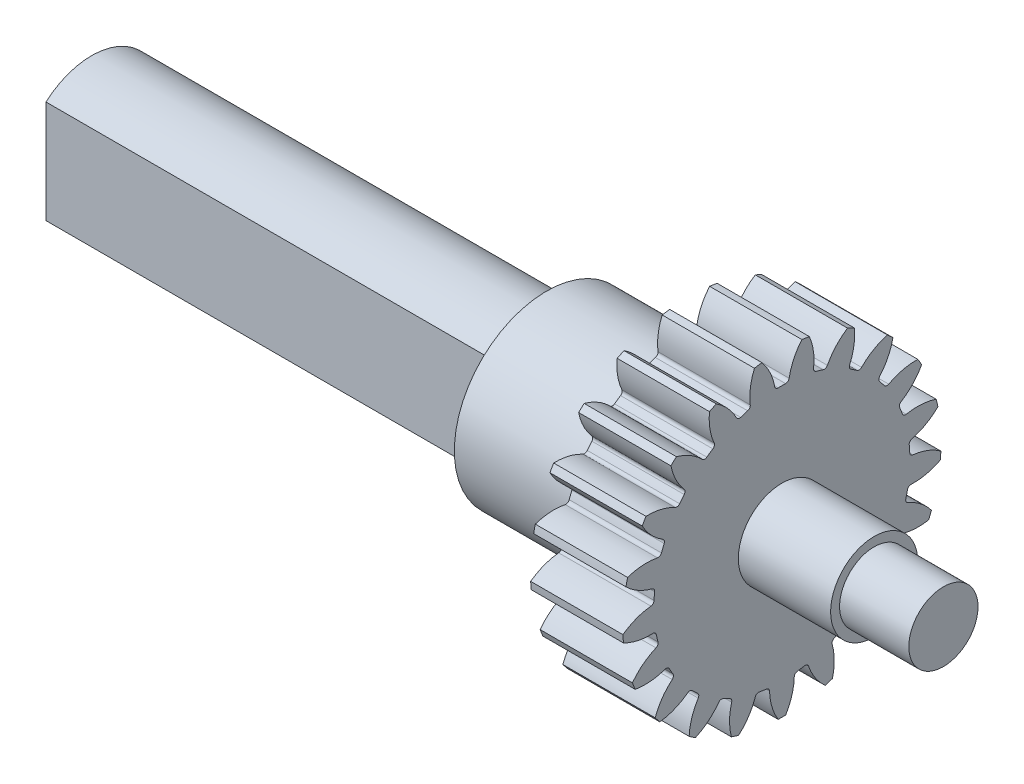
SolidWorks part; units mm, degrees
material "1.7003 (38Cr2)"
ref_plane "Plane1" through (0, 0, 0) normal (0, 0, 1) x (1, 0, 0)
ref_plane "Plane2" through (0, 0, 0) normal (0, 1, 0) x (1, 0, 0)
ref_plane "Plane3" through (0, 0, 0) normal (1, 0, 0) x (0, 0, -1)
sketch "BasProSke" plane through (0, 0, 0) normal (0, 1, 0) x (1, 0, 0)
  line L0 (-10, 0) -> (60, 0) construction
  line L1 (0, 0) -> (0, 3.45)
  line L2 (0, 0) -> (2, 0)
  line L3 (2, 0) -> (2, 3.45)
  line L4 (2, 3.45) -> (0, 3.45)
  dimension "Diameter" = 6.9
  dimension "Thickness" = 2
revolve "Base-Revolve" add sketch "BasProSke" angle 360 about L0
sketch "TooCutSke" plane through (0, 0, 0) normal (1, 0, 0) x (0, 0, -1)
  line L1 (0, 0) -> (0, 107) construction
  line L2 (0, 0) -> (-0.2529, 3.1398) construction
  line L3 (0, 0) -> (-0.9367, 6.2147) construction
  line L4 (-0.2529, 3.1398) -> (-0.4684, 3.1074) construction
  arc A0 (0.1463, 2.7701) -> (-0.1463, 2.7701) centre (0, 0) ccw
  arc A1 (0.4531, 3.4457) -> (-0.4531, 3.4457) centre (0, 0) ccw
  circle A2 centre (0, 0) radius 3.15 construction
  circle A3 centre (0, 0) radius 2.96 construction
  arc A4 (-0.1463, 2.7701) -> (-0.4531, 3.4457) centre (-1.3961, 2.6101) ccw
  arc A5 (0.4531, 3.4457) -> (0.1463, 2.7701) centre (1.3961, 2.6101) ccw
  dimension "Root_dia" = 5.548
  dimension "Overcut_dia" = 6.9508
  dimension "Pitch_dia" = 6.3
  dimension "Base_dia" = 5.9201
  dimension "Flank_rad" = 1.26
  dimension "Half_ang" = 8.571
  dimension "Half_CT" = 0.2179
extrude "ToothCut" cut sketch "TooCutSke" along normal through all
fillet "RootFillets" radius 0.076 2 edges at (1, 2.7701, -0.1463) (1, 2.7701, 0.1463)
pattern_circular "TeethCuts" count 21 over 360 about axis through (0, 0, 0) along (1, 0, 0) of "ToothCut", "RootFillets"
sketch "AxisSke" plane through (0, 0, 0) normal (-1, 0, 0) x (0, 0, 1)
  line L0 (0.99, 1.1136) -> (0.99, -1.1136)
  arc A0 (0.99, 1.1136) -> (0.99, -1.1136) centre (0, 0) ccw
  point P5 (-1.49, 0)
  dimension "D1" = 2.98
  dimension "D2" = 2.48
extrude "Axis" add sketch "AxisSke" along normal blind 12.96
sketch "Axis2Ske" plane through (2, 0, 0) normal (1, 0, 0) x (0, 0, -1)
  circle A0 centre (0, 0) radius 0.9445
  dimension "D1" = 1.889
extrude "Axis2" add sketch "Axis2Ske" along normal blind 2
sketch "Axis3Ske" plane through (4, 0, 0) normal (1, 0, 0) x (0, 0, -1)
  circle A0 centre (0, 0) radius 0.75
  dimension "D1" = 1.5
extrude "Axis3" add sketch "Axis3Ske" along normal blind 1.5
sketch "PadSke" plane through (0, 0, 0) normal (-1, 0, 0) x (0, 0, 1)
  circle A0 centre (0, 0) radius 2
  dimension "D1" = 4
extrude "Pad" add sketch "PadSke" along normal blind 3.1
equation "\"OAL@HoldingSke\" = \"Thickness@HoldingSke\""
equation "\"MHD@HoldingSke\" = (\"Num_teeth@HoldingSke\" + 2) / \"Pitch@HoldingSke\" - 2 * (\"Addendum_fac@HoldingSke\" + \"Dedendum_fac@HoldingSke\")  / \"Pitch@HoldingSke\" - \"Dedendum_add@HoldingSke\" * 2"
equation "\"MBD@HoldingSke\" = (\"Num_teeth@HoldingSke\" + 2) / \"Pitch@HoldingSke\" - 2 * (\"Addendum_fac@HoldingSke\" + \"Dedendum_fac@HoldingSke\")  / \"Pitch@HoldingSke\" - \"Dedendum_add@HoldingSke\" * 2 - 0.002 * 25.4"
equation "\"MHD@HoldingSke\" = ((sgn( \"MHD@HoldingSke\" - \"Hub_dia@HoldingSke\" )-1)*( \"MHD@HoldingSke\" - \"Hub_dia@HoldingSke\" ))/-2+ \"Hub_dia@HoldingSke\""
equation "\"Num_teeth@TeethCuts\" = int( \"Show_teeth@HoldingSke\" ) + 1"
equation "\"Num_teeth@TeethCuts\" = ((sgn( \"Num_teeth@TeethCuts\" - \"Num_teeth@HoldingSke\" )-1)*( \"Num_teeth@TeethCuts\" - \"Num_teeth@HoldingSke\" ))/-2+ \"Num_teeth@HoldingSke\""
